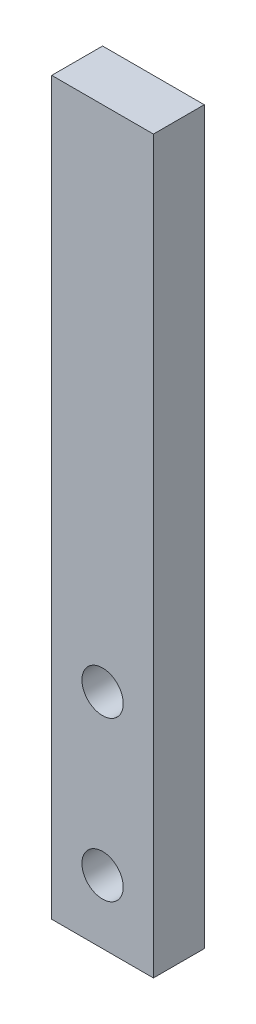
SolidWorks part; units mm, degrees
ref_plane "Front Plane" through (0, 0, 0) normal (0, 0, 1) x (1, 0, 0)
ref_plane "Top Plane" through (0, 0, 0) normal (0, 1, 0) x (1, 0, 0)
ref_plane "Right Plane" through (0, 0, 0) normal (1, 0, 0) x (0, 0, -1)
sketch "Sketch1" plane through (0, 0, 0) normal (0, 0, 1) x (1, 0, 0)
  line L0 (0, -111.932) -> (0, 93.2216)
  line L2 (8, -57.5) -> (-8, -57.5)
  line L3 (8, -57.5) -> (8, 57.5)
  line L4 (8, 57.5) -> (-8, 57.5)
  line L5 (-8, -57.5) -> (-8, 57.5)
  line L6 (8, -57.5) -> (-8, 57.5) construction
  line L7 (8, 57.5) -> (-8, -57.5) construction
  point P3 (0, 0)
extrude "Boss-Extrude1" add sketch "Sketch1" along normal blind 8 contours L3 L4 L5 L2
sketch "Sketch2" plane through (0, 0, 8) normal (0, 0, 1) x (1, 0, 0)
  circle A0 centre (0, -22.5) radius 3.25
  circle A1 centre (0, -47.5) radius 3.25
  dimension "D1" = 10
  dimension "D3" = 6.5
  dimension "D5" = 6.5
  dimension "D2" = 8
  dimension "D4" = 35
extrude "Cut-Extrude1" cut sketch "Sketch2" against normal through all
